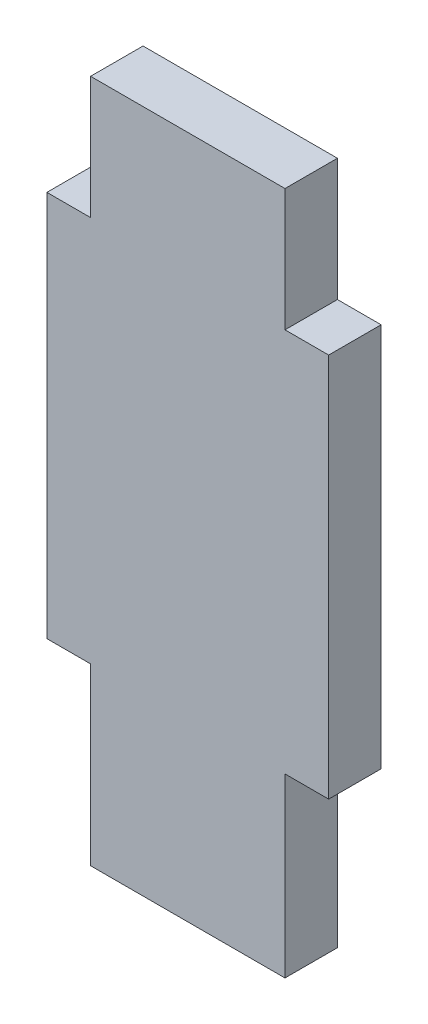
SolidWorks part; units mm, degrees
ref_plane "Front" through (0, 0, 0) normal (0, 0, 1) x (1, 0, 0)
ref_plane "Top" through (0, 0, 0) normal (0, 1, 0) x (1, 0, 0)
ref_plane "Right" through (0, 0, 0) normal (1, 0, 0) x (0, 0, -1)
sketch "Sketch1" plane through (0, 0, 0) normal (0, 0, 1) x (1, 0, 0)
  line L0 (704.3925, -103.808) -> (701.8925, -103.808)
  line L1 (718.0115, -81.6979) -> (718.0115, -103.6979)
  line L3 (715.5125, -113.808) -> (715.5125, -103.6979)
  line L4 (704.3925, -113.808) -> (704.3925, -103.808)
  line L5 (715.5125, -113.808) -> (704.3925, -113.808)
  line L6 (701.8925, -103.808) -> (701.8925, -81.6979)
  line L7 (715.5125, -81.6979) -> (718.0115, -81.6979)
  line L8 (715.5125, -103.6979) -> (718.0115, -103.6979)
  line L9 (715.5125, -74.6979) -> (715.5125, -81.6979)
  line L10 (704.3925, -74.6979) -> (715.5125, -74.6979)
  line L11 (701.8925, -81.6979) -> (704.3925, -81.6979)
  line L13 (704.3925, -81.6979) -> (704.3925, -74.6979)
  dimension "D5" = 2.4989
  dimension "D9" = 2.5
extrude "Base-Extrude" add sketch "Sketch1" along normal blind 3
